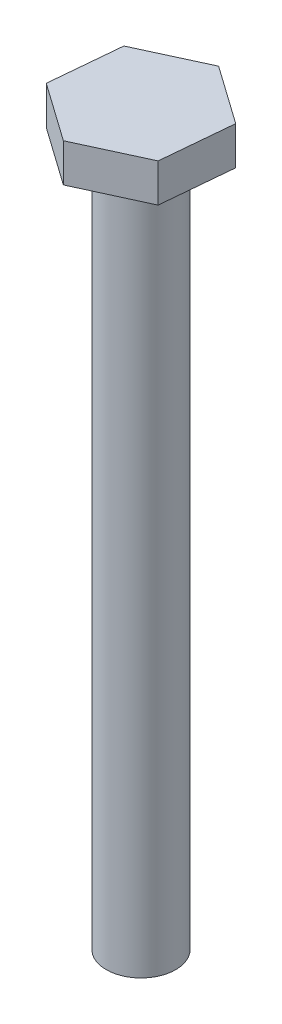
SolidWorks part; units mm, degrees
material "AISI 316 Stainless Steel Sheet (SS)"
ref_plane "Front Plane" through (0, 0, 0) normal (0, 0, 1) x (1, 0, 0)
ref_plane "Top Plane" through (0, 0, 0) normal (0, 1, 0) x (1, 0, 0)
ref_plane "Right Plane" through (0, 0, 0) normal (1, 0, 0) x (0, 0, -1)
sketch "Sketch2" plane through (0, 0, 0) normal (0, 1, 0) x (1, 0, 0)
  circle A0 centre (0, 0) radius 6.35
  dimension "D1" = 12.7
extrude "Boss-Extrude1" add sketch "Sketch2" against normal blind 127
sketch "Sketch3" plane through (0, 0, 0) normal (0, 1, 0) x (1, 0, 0)
  line L1 (10.6617, -7.5333) -> (11.8549, 5.4667)
  line L2 (11.8549, 5.4667) -> (1.1932, 13)
  line L3 (1.1932, 13) -> (-10.6617, 7.5333)
  line L4 (-10.6617, 7.5333) -> (-11.8549, -5.4667)
  line L5 (-11.8549, -5.4667) -> (-1.1932, -13)
  line L6 (-1.1932, -13) -> (10.6617, -7.5333)
  circle A0 centre (0, 0) radius 11.3057 construction
  dimension "D1" = 13
extrude "Boss-Extrude2" add sketch "Sketch3" along normal blind 7
equation "\"boltDiameter\"= 1in / 2"
equation "\"boltLength\"= 5in"
equation "\"D1@Sketch2\"=\"boltDiameter\""
equation "\"D1@Boss-Extrude1\"=\"boltLength\""
